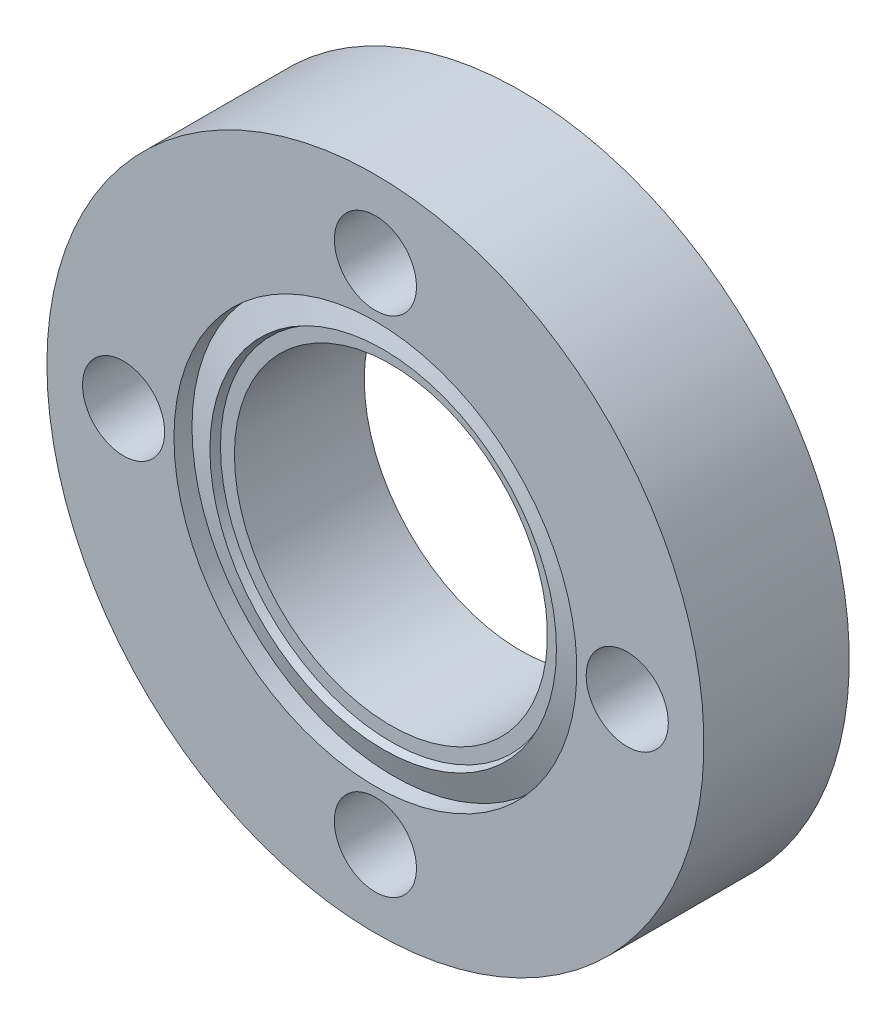
SolidWorks part; units mm, degrees
ref_plane "PL-01 Front" through (0, 0, 0) normal (0, 0, 1) x (1, 0, 0)
ref_plane "PL-02 Top" through (0, 0, 0) normal (0, 1, 0) x (1, 0, 0)
ref_plane "PL-03 Right" through (0, 0, 0) normal (1, 0, 0) x (0, 0, -1)
sketch "Sketch1" plane through (0, 0, 0) normal (1, 0, 0) x (0, 0, -1)
  line L0 (0, 0) -> (-76.5674, 0) construction
  line L1 (-1.27, 26.924) -> (10.6426, 26.924)
  line L2 (10.6426, 26.924) -> (10.6426, 12.827)
  line L3 (10.6426, 12.827) -> (0, 12.827)
  line L6 (0, 12.827) -> (0, 13.97)
  line L8 (0, 13.97) -> (-0.635, 14.2011)
  line L9 (-0.635, 14.2011) -> (0.2054, 16.51)
  line L11 (0.2054, 16.51) -> (-1.27, 16.51)
  line L12 (-1.27, 16.51) -> (-1.27, 26.924)
  dimension "D1" = 53.848
  dimension "D2" = 25.654
  dimension "D3" = 1.27
  dimension "D4" = 20
  dimension "D5" = 0.635
  dimension "D6" = 33.02
  dimension "D7" = 27.94
  dimension "D8" = 11.9126
revolve "Revolve1" add sketch "Sketch1" angle 360 about L0
sketch "Sketch2" plane through (0, 0, 0) normal (0, 0, 1) x (1, 0, 0)
  circle A0 centre (0, 20.6375) radius 3.3655
  dimension "D1" = 6.731
  dimension "D2" = 20.6375
extrude "Cut-Extrude1" cut sketch "Sketch2" against normal blind 19.05 and the other way blind 19.05
pattern_circular "CirPattern1" count 4 over 360 about axis through (0, 0, 0) along (0, 0, 1) of "Cut-Extrude1"
